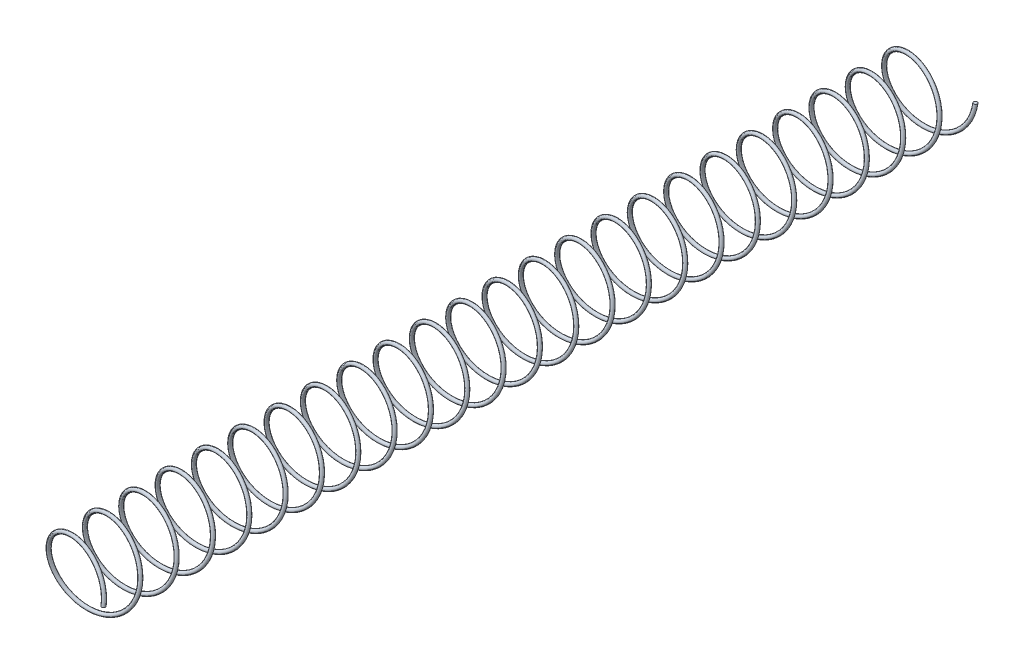
SolidWorks part; units mm, degrees
ref_plane "Front Plane" through (0, 0, 0) normal (0, 0, 1) x (1, 0, 0)
ref_plane "Top Plane" through (0, 0, 0) normal (0, 1, 0) x (1, 0, 0)
ref_plane "Right Plane" through (0, 0, 0) normal (1, 0, 0) x (0, 0, -1)
sketch "Sketch2" plane through (0, 0, 0) normal (0, 0, 1) x (1, 0, 0)
  circle A0 centre (0, 0) radius 25.4
  dimension "D1" = 50.8
curve "Helix/Spiral1" pitch 25.4 height 609.6 turns 24
sketch "Sketch3" plane through (0, 0, 0) normal (0, 1, 0) x (1, 0, 0)
  circle A0 centre (25.4, 0) radius 1.2954
  spline S0 degree 3 poles (25.4, 0) (25.4, -0.3758) (24.733, -1.1315) (21.8091, -2.2618) (17.1893, -3.393) (11.2329, -4.5239) (4.4029, -5.6549) (-2.7694, -6.7859) (-9.7264, -7.9169) (-15.927, -9.0479) (-20.8892, -10.1788) (-24.2269, -11.3098) (-25.6806, -12.4408) (-25.1374, -13.5718) (-22.6395, -14.7028) (-18.381, -15.8338) (-12.6932, -16.9647) (-6.0183, -18.0957) (1.1246, -19.2267) (8.18, -20.3577) (14.5993, -21.4887) (19.8834, -22.6197) (23.6212, -23.7506) (25.5222, -24.8816) (25.4386, -26.0126) (23.3768, -27.1436) (19.4971, -28.2746) (14.1013, -29.4056) (7.609, -30.5365) (0.5249, -31.6675) (-6.5999, -32.7985) (-13.2116, -33.9295) (-18.7958, -35.0605) (-22.9185, -36.1915) (-25.259, -37.3224) (-25.6352, -38.4534) (-24.018, -39.5844) (-20.5331, -40.7154) (-15.4515, -41.8464) (-9.1684, -42.9774) (-2.1723, -44.1083) (4.9928, -45.2393) (11.7696, -46.3703) (17.6311, -47.5013) (22.1216, -48.6323) (24.8919, -49.7633) (25.7265, -50.8942) (24.5606, -52.0252) (21.4848, -53.1562) (16.7382, -54.2872) (10.6901, -55.4182) (3.8107, -56.5492) (-3.3651, -57.6801) (-10.2792, -58.8111) (-16.3939, -59.9421) (-21.2338, -61.0731) (-24.4225, -62.2041) (-25.7121, -63.3351) (-25.0022, -64.466) (-22.3481, -65.597) (-17.9562, -66.728) (-12.1679, -67.859) (-5.4334, -68.99) (1.7236, -70.121) (8.7465, -71.2519) (15.0894, -72.3829) (20.2588, -73.5139) (23.8528, -74.6449) (25.592, -75.7759) (25.3411, -76.9069) (23.1196, -78.0378) (19.1003, -79.1688) (13.5957, -80.2998) (7.0338, -81.4308) (-0.075, -82.5618) (-7.178, -83.6928) (-13.7228, -84.8237) (-19.2005, -85.9547) (-23.1851, -87.0857) (-25.3668, -88.2167) (-25.5759, -89.3477) (-23.7961, -90.4787) (-20.1659, -91.6096) (-14.9676, -92.7406) (-8.6053, -93.8716) (-1.5739, -95.0026) (5.5799, -96.1336) (12.2998, -97.2646) (18.0633, -98.3955) (22.4221, -99.5265) (25.0373, -100.6575) (25.7055, -101.7885) (24.3749, -102.9195) (21.1487, -104.0505) (16.278, -105.1814) (10.1415, -106.3124) (3.2163, -107.4434) (-3.9589, -108.5744) (-10.8263, -109.7054) (-16.8519, -110.8364) (-21.567, -111.9673) (-24.6049, -113.0983) (-25.7296, -114.2293) (-24.8534, -115.3603) (-22.0446, -116.4913) (-17.5216, -117.6223) (-11.636, -118.7532) (-4.8456, -119.8842) (2.3217, -121.0152) (9.3084, -122.1462) (15.5712, -123.2772) (20.6232, -124.4082) (24.0715, -125.5391) (25.6479, -126.6701) (25.2299, -127.8011) (22.8499, -128.9321) (18.6931, -130.0631) (13.0826, -131.1941) (6.4549, -132.325) (-0.6749, -133.456) (-7.7521, -134.587) (-14.2265, -135.718) (-19.5947, -136.849) (-23.4391, -137.98) (-25.4608, -139.1109) (-25.5026, -140.2419) (-23.5613, -141.3729) (-19.7878, -142.5039) (-14.4755, -143.6349) (-8.0376, -144.7659) (-0.9747, -145.8968) (6.164, -147.0278) (12.8234, -148.1588) (18.4857, -149.2898) (22.7104, -150.4208) (25.1691, -151.5518) (25.6706, -152.6827) (24.1759, -153.8137) (20.8012, -154.9447) (15.809, -156.0757) (9.5874, -157.2067) (2.6203, -158.3377) (-4.5506, -159.4686) (-11.3676, -160.5996) (-17.3007, -161.7306) (-21.8884, -162.8616) (-24.774, -163.9926) (-25.7331, -165.1236) (-24.6911, -166.2545) (-21.7291, -167.3855) (-17.0774, -168.5165) (-11.0977, -169.6475) (-4.2551, -170.7785) (2.9185, -171.9095) (9.8651, -173.0404) (16.0446, -174.1714) (20.9764, -175.3024) (24.277, -176.4334) (25.6898, -177.5644) (25.1049, -178.6954) (22.5678, -179.8263) (18.2757, -180.9573) (12.5625, -182.0883) (5.8724, -183.2193) (-1.2744, -184.3503) (-8.3221, -185.4813) (-14.7226, -186.6122) (-19.9782, -187.7432) (-23.6803, -188.8742) (-25.541, -190.0052) (-25.4155, -191.1362) (-23.3137, -192.2672) (-19.3989, -193.3981) (-13.9756, -194.5291) (-7.4656, -195.6601) (-0.375, -196.7911) (6.7448, -197.9221) (13.3401, -199.0531) (18.898, -200.184) (22.9863, -201.315) (25.2872, -202.446) (25.6217, -203.577) (23.9638, -204.708) (20.4424, -205.839) (15.3313, -206.9699) (9.0281, -208.1009) (2.0228, -209.2319) (-5.1398, -210.3629) (-11.9027, -211.4939) (-17.7401, -212.6249) (-22.1979, -213.7558) (-24.9295, -214.8868) (-25.7226, -216.0178) (-24.5154, -217.1488) (-21.4018, -218.2798) (-16.624, -219.4108) (-10.5535, -220.5417) (-3.6623, -221.6727) (3.5137, -222.8037) (10.4165, -223.9347) (16.5092, -225.0657) (21.3182, -226.1967) (24.4694, -227.3276) (25.7178, -228.4586) (24.9663, -229.5896) (22.2734, -230.7206) (17.8484, -231.8516) (12.0355, -232.9826) (5.2867, -234.1135) (-1.8732, -235.2445) (-8.8875, -236.3755) (-15.2106, -237.5065) (-20.3509, -238.6375) (-23.9087, -239.7685) (-25.6073, -240.8994) (-25.3146, -242.0304) (-23.0534, -243.1614) (-18.9995, -244.2924) (-13.4681, -245.4234) (-6.8894, -246.5544) (0.225, -247.6853) (7.3219, -248.8163) (13.8494, -249.9473) (19.3, -251.0783) (23.2498, -252.2093) (25.3916, -253.3403) (25.5589, -254.4712) (23.7386, -255.6022) (20.0724, -256.7332) (14.8453, -257.8642) (8.4638, -258.9952) (1.4242, -260.1262) (-5.7262, -261.2571) (-12.4314, -262.3881) (-18.1698, -263.5191) (-22.4953, -264.6501) (-25.0715, -265.7811) (-25.6981, -266.9121) (-24.3264, -268.043) (-21.0629, -269.174) (-16.1616, -270.305) (-10.0035, -271.436) (-3.0675, -272.567) (4.1071, -273.698) (10.9622, -274.8289) (16.9649, -275.9599) (21.6484, -277.0909) (24.6485, -278.2219) (25.7318, -279.3529) (24.8141, -280.4839) (21.9669, -281.6148) (17.4114, -282.7458) (11.502, -283.8768) (4.6982, -285.0078) (-2.471, -286.1388) (-9.448, -287.2698) (-15.6904, -288.4007) (-20.7126, -289.5317) (-24.1241, -290.6627) (-25.6597, -291.7937) (-25.1999, -292.9247) (-22.7805, -294.0557) (-18.5897, -295.1866) (-12.9533, -296.3176) (-6.3096, -297.4486) (0.8248, -298.5796) (7.895, -299.7106) (14.3513, -300.8416) (19.6916, -301.9725) (23.5006, -303.1035) (25.4822, -304.2345) (25.4822, -305.3655) (23.5006, -306.4965) (19.6916, -307.6275) (14.3513, -308.7584) (7.895, -309.8894) (0.8248, -311.0204) (-6.3096, -312.1514) (-12.9533, -313.2824) (-18.5897, -314.4134) (-22.7805, -315.5443) (-25.1999, -316.6753) (-25.6597, -317.8063) (-24.1241, -318.9373) (-20.7126, -320.0683) (-15.6904, -321.1993) (-9.448, -322.3302) (-2.471, -323.4612) (4.6982, -324.5922) (11.502, -325.7232) (17.4114, -326.8542) (21.9669, -327.9852) (24.8141, -329.1161) (25.7318, -330.2471) (24.6485, -331.3781) (21.6484, -332.5091) (16.9649, -333.6401) (10.9622, -334.7711) (4.1071, -335.902) (-3.0675, -337.033) (-10.0035, -338.164) (-16.1616, -339.295) (-21.0629, -340.426) (-24.3264, -341.557) (-25.6981, -342.6879) (-25.0715, -343.8189) (-22.4953, -344.9499) (-18.1698, -346.0809) (-12.4314, -347.2119) (-5.7262, -348.3429) (1.4242, -349.4738) (8.4638, -350.6048) (14.8453, -351.7358) (20.0724, -352.8668) (23.7386, -353.9978) (25.5589, -355.1288) (25.3916, -356.2597) (23.2498, -357.3907) (19.3, -358.5217) (13.8494, -359.6527) (7.3219, -360.7837) (0.225, -361.9147) (-6.8894, -363.0456) (-13.4681, -364.1766) (-18.9995, -365.3076) (-23.0534, -366.4386) (-25.3146, -367.5696) (-25.6073, -368.7006) (-23.9087, -369.8315) (-20.3509, -370.9625) (-15.2106, -372.0935) (-8.8875, -373.2245) (-1.8732, -374.3555) (5.2867, -375.4865) (12.0355, -376.6174) (17.8484, -377.7484) (22.2734, -378.8794) (24.9663, -380.0104) (25.7178, -381.1414) (24.4694, -382.2724) (21.3182, -383.4033) (16.5092, -384.5343) (10.4165, -385.6653) (3.5137, -386.7963) (-3.6623, -387.9273) (-10.5535, -389.0583) (-16.624, -390.1892) (-21.4018, -391.3202) (-24.5154, -392.4512) (-25.7226, -393.5822) (-24.9295, -394.7132) (-22.1979, -395.8442) (-17.7401, -396.9751) (-11.9027, -398.1061) (-5.1398, -399.2371) (2.0228, -400.3681) (9.0281, -401.4991) (15.3313, -402.6301) (20.4424, -403.761) (23.9638, -404.892) (25.6217, -406.023) (25.2872, -407.154) (22.9863, -408.285) (18.898, -409.416) (13.3401, -410.5469) (6.7448, -411.6779) (-0.375, -412.8089) (-7.4656, -413.9399) (-13.9756, -415.0709) (-19.3989, -416.2019) (-23.3137, -417.3328) (-25.4155, -418.4638) (-25.541, -419.5948) (-23.6803, -420.7258) (-19.9782, -421.8568) (-14.7226, -422.9878) (-8.3221, -424.1187) (-1.2744, -425.2497) (5.8724, -426.3807) (12.5625, -427.5117) (18.2757, -428.6427) (22.5678, -429.7737) (25.1049, -430.9046) (25.6898, -432.0356) (24.277, -433.1666) (20.9764, -434.2976) (16.0446, -435.4286) (9.8651, -436.5596) (2.9185, -437.6905) (-4.2551, -438.8215) (-11.0977, -439.9525) (-17.0774, -441.0835) (-21.7291, -442.2145) (-24.6911, -443.3455) (-25.7331, -444.4764) (-24.774, -445.6074) (-21.8884, -446.7384) (-17.3007, -447.8694) (-11.3676, -449.0004) (-4.5506, -450.1314) (2.6203, -451.2623) (9.5874, -452.3933) (15.809, -453.5243) (20.8012, -454.6553) (24.1759, -455.7863) (25.6706, -456.9173) (25.1691, -458.0482) (22.7104, -459.1792) (18.4857, -460.3102) (12.8234, -461.4412) (6.164, -462.5722) (-0.9747, -463.7032) (-8.0376, -464.8341) (-14.4755, -465.9651) (-19.7878, -467.0961) (-23.5613, -468.2271) (-25.5026, -469.3581) (-25.4608, -470.4891) (-23.4391, -471.62) (-19.5947, -472.751) (-14.2265, -473.882) (-7.7521, -475.013) (-0.6749, -476.144) (6.4549, -477.275) (13.0826, -478.4059) (18.6931, -479.5369) (22.8499, -480.6679) (25.2299, -481.7989) (25.6479, -482.9299) (24.0715, -484.0609) (20.6232, -485.1918) (15.5712, -486.3228) (9.3084, -487.4538) (2.3217, -488.5848) (-4.8456, -489.7158) (-11.636, -490.8468) (-17.5216, -491.9777) (-22.0446, -493.1087) (-24.8534, -494.2397) (-25.7296, -495.3707) (-24.6049, -496.5017) (-21.567, -497.6327) (-16.8519, -498.7636) (-10.8263, -499.8946) (-3.9589, -501.0256) (3.2163, -502.1566) (10.1415, -503.2876) (16.278, -504.4186) (21.1487, -505.5495) (24.3749, -506.6805) (25.7055, -507.8115) (25.0373, -508.9425) (22.4221, -510.0735) (18.0633, -511.2045) (12.2998, -512.3354) (5.5799, -513.4664) (-1.5739, -514.5974) (-8.6053, -515.7284) (-14.9676, -516.8594) (-20.1659, -517.9904) (-23.7961, -519.1213) (-25.5759, -520.2523) (-25.3668, -521.3833) (-23.1851, -522.5143) (-19.2005, -523.6453) (-13.7228, -524.7763) (-7.178, -525.9072) (-0.075, -527.0382) (7.0338, -528.1692) (13.5957, -529.3002) (19.1003, -530.4312) (23.1196, -531.5622) (25.3411, -532.6931) (25.592, -533.8241) (23.8528, -534.9551) (20.2588, -536.0861) (15.0894, -537.2171) (8.7465, -538.3481) (1.7236, -539.479) (-5.4334, -540.61) (-12.1679, -541.741) (-17.9562, -542.872) (-22.3481, -544.003) (-25.0022, -545.134) (-25.7121, -546.2649) (-24.4225, -547.3959) (-21.2338, -548.5269) (-16.3939, -549.6579) (-10.2792, -550.7889) (-3.3651, -551.9199) (3.8107, -553.0508) (10.6901, -554.1818) (16.7382, -555.3128) (21.4848, -556.4438) (24.5606, -557.5748) (25.7265, -558.7058) (24.8919, -559.8367) (22.1216, -560.9677) (17.6311, -562.0987) (11.7696, -563.2297) (4.9928, -564.3607) (-2.1723, -565.4917) (-9.1684, -566.6226) (-15.4515, -567.7536) (-20.5331, -568.8846) (-24.018, -570.0156) (-25.6352, -571.1466) (-25.259, -572.2776) (-22.9185, -573.4085) (-18.7958, -574.5395) (-13.2116, -575.6705) (-6.5999, -576.8015) (0.5249, -577.9325) (7.609, -579.0635) (14.1013, -580.1944) (19.4971, -581.3254) (23.3768, -582.4564) (25.4386, -583.5874) (25.5222, -584.7184) (23.6212, -585.8494) (19.8834, -586.9803) (14.5993, -588.1113) (8.18, -589.2423) (1.1246, -590.3733) (-6.0183, -591.5043) (-12.6932, -592.6353) (-18.381, -593.7662) (-22.6395, -594.8972) (-25.1374, -596.0282) (-25.6806, -597.1592) (-24.2269, -598.2902) (-20.8892, -599.4212) (-15.927, -600.5521) (-9.7264, -601.6831) (-2.7694, -602.8141) (4.4029, -603.9451) (11.2329, -605.0761) (17.1893, -606.207) (21.8091, -607.3382) (24.733, -608.4685) (25.4, -609.2242) (25.4, -609.6) knots 0 0 0 0 0.001855 0.003711 0.005566 0.007421 0.009276 0.011132 0.012987 0.014842 0.016698 0.018553 0.020408 0.022263 0.024119 0.025974 0.027829 0.029685 0.03154 0.033395 0.03525 0.037106 0.038961 0.040816 0.042672 0.044527 0.046382 0.048237 0.050093 0.051948 0.053803 0.055659 0.057514 0.059369 0.061224 0.06308 0.064935 0.06679 0.068646 0.070501 0.072356 0.074212 0.076067 0.077922 0.079777 0.081633 0.083488 0.085343 0.087199 0.089054 0.090909 0.092764 0.09462 0.096475 0.09833 0.100186 0.102041 0.103896 0.105751 0.107607 0.109462 0.111317 0.113173 0.115028 0.116883 0.118738 0.120594 0.122449 0.124304 0.12616 0.128015 0.12987 0.131725 0.133581 0.135436 0.137291 0.139147 0.141002 0.142857 0.144712 0.146568 0.148423 0.150278 0.152134 0.153989 0.155844 0.157699 0.159555 0.16141 0.163265 0.165121 0.166976 0.168831 0.170686 0.172542 0.174397 0.176252 0.178108 0.179963 0.181818 0.183673 0.185529 0.187384 0.189239 0.191095 0.19295 0.194805 0.19666 0.198516 0.200371 0.202226 0.204082 0.205937 0.207792 0.209647 0.211503 0.213358 0.215213 0.217069 0.218924 0.220779 0.222635 0.22449 0.226345 0.2282 0.230056 0.231911 0.233766 0.235622 0.237477 0.239332 0.241187 0.243043 0.244898 0.246753 0.248609 0.250464 0.252319 0.254174 0.25603 0.257885 0.25974 0.261596 0.263451 0.265306 0.267161 0.269017 0.270872 0.272727 0.274583 0.276438 0.278293 0.280148 0.282004 0.283859 0.285714 0.28757 0.289425 0.29128 0.293135 0.294991 0.296846 0.298701 0.300557 0.302412 0.304267 0.306122 0.307978 0.309833 0.311688 0.313544 0.315399 0.317254 0.319109 0.320965 0.32282 0.324675 0.326531 0.328386 0.330241 0.332096 0.333952 0.335807 0.337662 0.339518 0.341373 0.343228 0.345083 0.346939 0.348794 0.350649 0.352505 0.35436 0.356215 0.358071 0.359926 0.361781 0.363636 0.365492 0.367347 0.369202 0.371058 0.372913 0.374768 0.376623 0.378479 0.380334 0.382189 0.384045 0.3859 0.387755 0.38961 0.391466 0.393321 0.395176 0.397032 0.398887 0.400742 0.402597 0.404453 0.406308 0.408163 0.410019 0.411874 0.413729 0.415584 0.41744 0.419295 0.42115 0.423006 0.424861 0.426716 0.428571 0.430427 0.432282 0.434137 0.435993 0.437848 0.439703 0.441558 0.443414 0.445269 0.447124 0.44898 0.450835 0.45269 0.454545 0.456401 0.458256 0.460111 0.461967 0.463822 0.465677 0.467532 0.469388 0.471243 0.473098 0.474954 0.476809 0.478664 0.480519 0.482375 0.48423 0.486085 0.487941 0.489796 0.491651 0.493506 0.495362 0.497217 0.499072 0.500928 0.502783 0.504638 0.506494 0.508349 0.510204 0.512059 0.513915 0.51577 0.517625 0.519481 0.521336 0.523191 0.525046 0.526902 0.528757 0.530612 0.532468 0.534323 0.536178 0.538033 0.539889 0.541744 0.543599 0.545455 0.54731 0.549165 0.55102 0.552876 0.554731 0.556586 0.558442 0.560297 0.562152 0.564007 0.565863 0.567718 0.569573 0.571429 0.573284 0.575139 0.576994 0.57885 0.580705 0.58256 0.584416 0.586271 0.588126 0.589981 0.591837 0.593692 0.595547 0.597403 0.599258 0.601113 0.602968 0.604824 0.606679 0.608534 0.61039 0.612245 0.6141 0.615955 0.617811 0.619666 0.621521 0.623377 0.625232 0.627087 0.628942 0.630798 0.632653 0.634508 0.636364 0.638219 0.640074 0.641929 0.643785 0.64564 0.647495 0.649351 0.651206 0.653061 0.654917 0.656772 0.658627 0.660482 0.662338 0.664193 0.666048 0.667904 0.669759 0.671614 0.673469 0.675325 0.67718 0.679035 0.680891 0.682746 0.684601 0.686456 0.688312 0.690167 0.692022 0.693878 0.695733 0.697588 0.699443 0.701299 0.703154 0.705009 0.706865 0.70872 0.710575 0.71243 0.714286 0.716141 0.717996 0.719852 0.721707 0.723562 0.725417 0.727273 0.729128 0.730983 0.732839 0.734694 0.736549 0.738404 0.74026 0.742115 0.74397 0.745826 0.747681 0.749536 0.751391 0.753247 0.755102 0.756957 0.758813 0.760668 0.762523 0.764378 0.766234 0.768089 0.769944 0.7718 0.773655 0.77551 0.777365 0.779221 0.781076 0.782931 0.784787 0.786642 0.788497 0.790353 0.792208 0.794063 0.795918 0.797774 0.799629 0.801484 0.80334 0.805195 0.80705 0.808905 0.810761 0.812616 0.814471 0.816327 0.818182 0.820037 0.821892 0.823748 0.825603 0.827458 0.829314 0.831169 0.833024 0.834879 0.836735 0.83859 0.840445 0.842301 0.844156 0.846011 0.847866 0.849722 0.851577 0.853432 0.855288 0.857143 0.858998 0.860853 0.862709 0.864564 0.866419 0.868275 0.87013 0.871985 0.87384 0.875696 0.877551 0.879406 0.881262 0.883117 0.884972 0.886827 0.888683 0.890538 0.892393 0.894249 0.896104 0.897959 0.899814 0.90167 0.903525 0.90538 0.907236 0.909091 0.910946 0.912801 0.914657 0.916512 0.918367 0.920223 0.922078 0.923933 0.925788 0.927644 0.929499 0.931354 0.93321 0.935065 0.93692 0.938776 0.940631 0.942486 0.944341 0.946197 0.948052 0.949907 0.951763 0.953618 0.955473 0.957328 0.959184 0.961039 0.962894 0.96475 0.966605 0.96846 0.970315 0.972171 0.974026 0.975881 0.977737 0.979592 0.981447 0.983302 0.985158 0.987013 0.988868 0.990724 0.992579 0.994434 0.996289 0.998145 1 1 1 1 construction
  dimension "D1" = 2.5908
sweep "Sweep1" add profiles "Sketch3" path "Helix/Spiral1"
